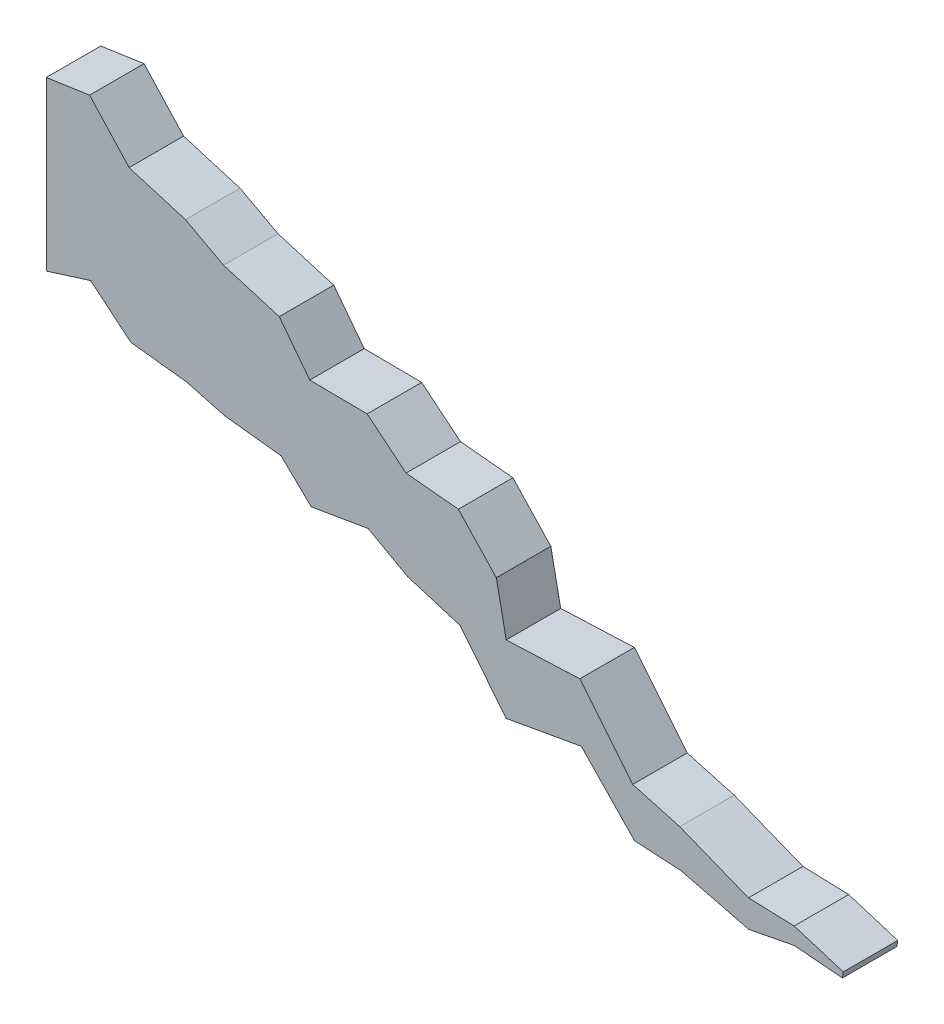
SolidWorks part; units mm, degrees
ref_plane "Ebene vorne" through (0, 0, 0) normal (0, 0, 1) x (1, 0, 0)
ref_plane "Ebene oben" through (0, 0, 0) normal (0, 1, 0) x (1, 0, 0)
ref_plane "Ebene rechts" through (0, 0, 0) normal (1, 0, 0) x (0, 0, -1)
sketch "Model" plane through (0, 0, 0) normal (0, 0, 1) x (1, 0, 0)
  line L37 (0.1, 21.3829) -> (2.4837, 21.7325)
  line L38 (2.4837, 21.7325) -> (4.6604, 19.365)
  line L39 (4.6604, 19.365) -> (7.7668, 18.4383)
  line L40 (7.7668, 18.4383) -> (9.8602, 17.3103)
  line L41 (9.8602, 17.3103) -> (12.9288, 16.3947)
  line L42 (12.9288, 16.3947) -> (14.6092, 14.2071)
  line L43 (14.6092, 14.2071) -> (17.768, 14.1759)
  line L44 (17.768, 14.1759) -> (19.9079, 12.4219)
  line L45 (19.9079, 12.4219) -> (22.7918, 12.1414)
  line L46 (22.7918, 12.1414) -> (24.8803, 9.917)
  line L47 (24.8803, 9.917) -> (25.4247, 7.225)
  line L48 (25.4247, 7.225) -> (29.4781, 7.3964)
  line L49 (29.4781, 7.3964) -> (32.3899, 3.8165)
  line L50 (32.3899, 3.8165) -> (34.9819, 3.0991)
  line L51 (34.9819, 3.0991) -> (38.7622, 1.594)
  line L52 (38.7622, 1.594) -> (41.2825, 1.5125)
  line L53 (41.2825, 1.5125) -> (43.9822, 0.6741)
  line L54 (43.9822, 0.6741) -> (43.9363, 0.3596)
  line L55 (43.9363, 0.3596) -> (41.2939, 0.5839)
  line L56 (41.2939, 0.5839) -> (38.7857, 0.1024)
  line L57 (38.7857, 0.1024) -> (35.0288, 1.0355)
  line L58 (35.0288, 1.0355) -> (32.4921, 1.1798)
  line L59 (32.4921, 1.1798) -> (29.5589, 4.2196)
  line L60 (29.5589, 4.2196) -> (27.8812, 3.92)
  line L61 (27.8812, 3.92) -> (26.3129, 3.64)
  line L62 (26.3129, 3.64) -> (25.423, 3.4811)
  line L63 (25.423, 3.4811) -> (22.8849, 6.6444)
  line L64 (22.8849, 6.6444) -> (19.9872, 7.531)
  line L65 (19.9872, 7.531) -> (17.8221, 8.7356)
  line L66 (17.8221, 8.7356) -> (14.692, 8.2048)
  line L67 (14.692, 8.2048) -> (13.0335, 9.8034)
  line L68 (13.0335, 9.8034) -> (9.9174, 10.1639)
  line L69 (9.9174, 10.1639) -> (7.824, 10.7274)
  line L70 (7.824, 10.7274) -> (4.7564, 11.0822)
  line L71 (4.7564, 11.0822) -> (2.5435, 12.9197)
  line L72 (2.5435, 12.9197) -> (0.1, 12.1505)
  line L73 (0.1, 12.1505) -> (0.1, 21.3829)
extrude "Aufsatz-Linear austragen1" add sketch "Model" along normal blind 3 contours L37 L38 L39 L40 L41 L42 L43 L44 L45 L46 L47 L48 L49 L50 L51 L52 L53 L54 L55 L56 L57 L58 L59 L60 L61 L62 L63 L64 L65 L66 L67 L68 L69 L70 L71 L72 L73
